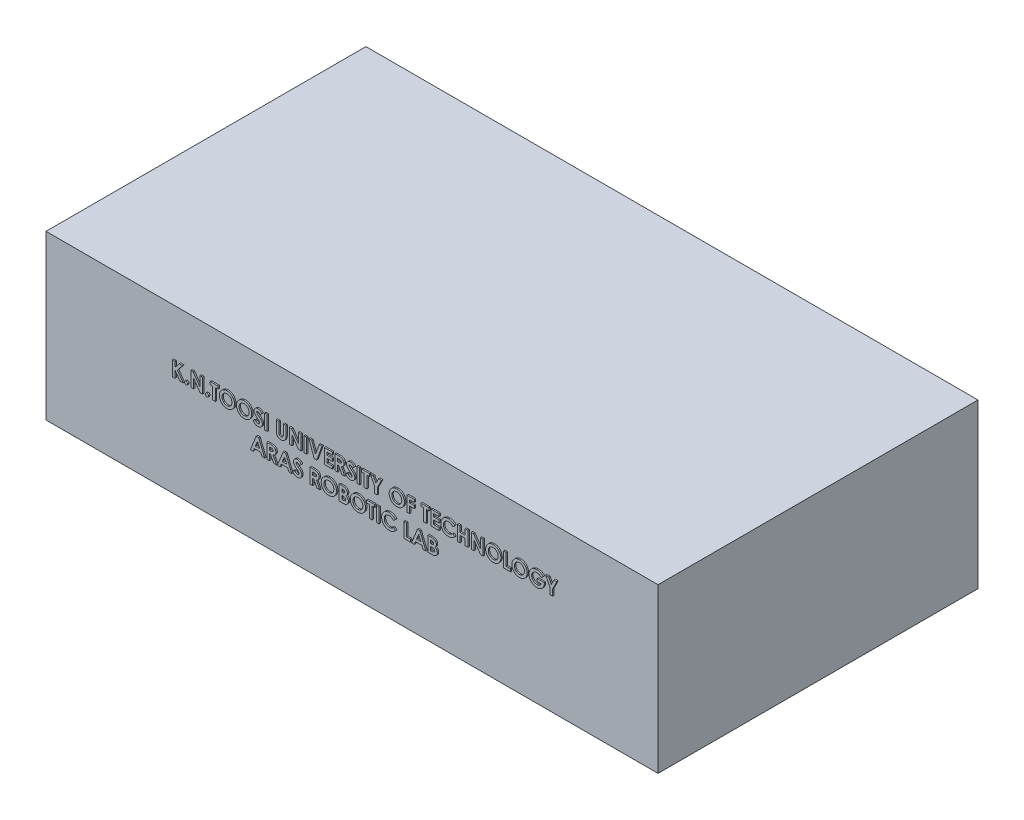
SolidWorks part; units mm, degrees
ref_plane "Front Plane" through (0, 0, 0) normal (0, 0, 1) x (1, 0, 0)
ref_plane "Top Plane" through (0, 0, 0) normal (0, 1, 0) x (1, 0, 0)
ref_plane "Right Plane" through (0, 0, 0) normal (1, 0, 0) x (0, 0, -1)
sketch "Sketch1" plane through (0, 0, 0) normal (0, 1, 0) x (1, 0, 0)
  line L1 (-1100, -575) -> (1100, -575)
  line L2 (-1100, -575) -> (-1100, 575)
  line L3 (-1100, 575) -> (1100, 575)
  line L4 (1100, -575) -> (1100, 575)
  line L5 (-1100, -575) -> (1100, 575) construction
  line L6 (-1100, 575) -> (1100, -575) construction
  point P0 (0, 0)
  dimension "D1" = 1150
  dimension "D2" = 2200
extrude "Boss-Extrude1" add sketch "Sketch1" along normal blind 587.4322
sketch "Sketch2" plane through (0, 0, 575) normal (0, 0, 1) x (1, 0, 0)
  text T0 "<b>K.N.TOOSI UNIVERSITY OF TECHNOLOGY </b>\r\n<b>              ARAS ROBOTIC LAB</b>" font "Century Gothic" height in points 200
extrude "Boss-Extrude2" add sketch "Sketch2" along normal blind 5
